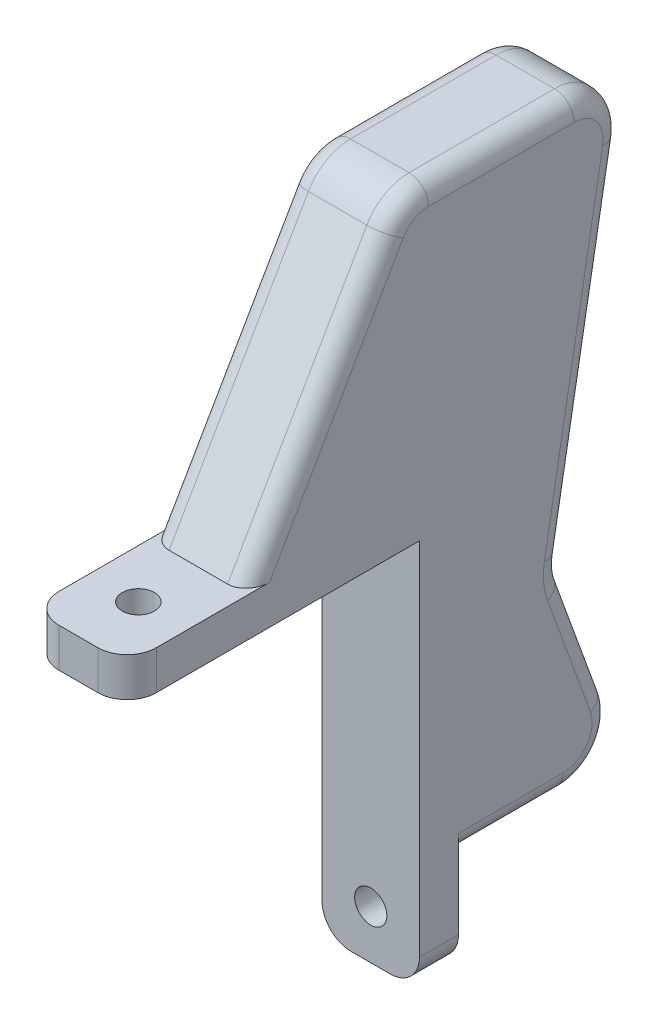
SolidWorks part; units mm, degrees
ref_plane "Front Plane" through (0, 0, 0) normal (0, 0, 1) x (1, 0, 0)
ref_plane "Top Plane" through (0, 0, 0) normal (0, 1, 0) x (1, 0, 0)
ref_plane "Right Plane" through (0, 0, 0) normal (1, 0, 0) x (0, 0, -1)
sketch "Sketch1" plane through (0, 0, 0) normal (1, 0, 0) x (0, 0, -1)
  line L0 (0, 0) -> (20, 0)
  line L1 (0, 0) -> (18.0413, 31.2484)
  line L2 (18.0413, 31.2484) -> (41.8095, 31.2484)
  line L4 (41.8684, -30) -> (20, -30)
  line L6 (20, 0) -> (20, -30)
  line L8 (20, -30) -> (32.0088, -30) construction
  line L9 (41.8095, 31.2484) -> (34.5535, -9.9026)
  line L10 (34.5535, -9.9026) -> (41.8684, -30)
  point P7 (34.5535, -9.9026)
  dimension "D1" = 20
  dimension "D2" = 60
  dimension "D3" = 70
  dimension "D4" = 80
  dimension "D7" = 30
extrude "Boss-Extrude1" add sketch "Sketch1" along normal blind 10
fillet "Fillet1" radius 5 4 edges at (5, -30, -41.8684) (5, -9.9026, -34.5535) (5, 31.2484, -41.8095) (5, 31.2484, -18.0413)
sketch "Sketch2" plane through (0, 0, 0) normal (0, -1, 0) x (1, 0, 0)
  line L0 (0, -20) -> (0, 0)
  line L1 (0, 0) -> (0, 10)
  line L2 (0, 10) -> (10, 10)
  line L3 (10, 10) -> (10, 0)
  line L4 (10, 0) -> (10, -20)
  line L5 (10, -20) -> (0, -20)
  line L6 (10, 0) -> (0, 0) construction
extrude "Boss-Extrude2" add sketch "Sketch2" against normal blind 4
sketch "Sketch3" plane through (0, 4, 0) normal (0, 1, 0) x (1, 0, 0)
  line L0 (5, -10) -> (5, 2.3094) construction
  line L1 (10, -10) -> (0, -10) construction
  line L2 (0, 2.3094) -> (10, 2.3094) construction
  circle A0 centre (5, -3.8453) radius 1.65
  dimension "D1" = 3.3
extrude "Cut-Extrude1" cut sketch "Sketch3" against normal through all
sketch "Sketch4" plane through (0, 0, -20) normal (0, 0, 1) x (1, 0, 0)
  line L0 (0, 0) -> (0, -30)
  line L1 (0, -30) -> (0, -40)
  line L2 (0, -40) -> (10, -40)
  line L3 (10, -40) -> (10, -30)
  line L4 (10, -30) -> (10, 0)
  line L5 (10, 0) -> (0, 0)
  line L6 (10, -30) -> (0, -30) construction
extrude "Boss-Extrude3" add sketch "Sketch4" against normal blind 4
sketch "Sketch5" plane through (0, 0, -24) normal (0, 0, -1) x (-1, 0, 0)
  line L0 (-5, -30) -> (-5, -40) construction
  line L1 (0, -30) -> (-10, -30) construction
  line L2 (0, -40) -> (-10, -40) construction
  circle A0 centre (-5, -35) radius 1.65
  dimension "D1" = 3.3
extrude "Cut-Extrude2" cut sketch "Sketch5" against normal through all
fillet "Fillet2" radius 3 4 edges at (0, -40, -22) (10, -40, -22) (0, 2, 10) (10, 2, 10)
fillet "Fillet3" radius 2 18 edges at (0, -30, -29.3638) (0, -27.8679, -38.8234) (0, -17.2257, -37.2189) (0, -9.8872, -34.7292) (0, 8.3985, -37.7805) (0, 29.4623, -39.681) (0, 31.2484, -28.3894) (0, 30.5785, -18.428) (10, -30, -29.3638) (10, -27.8679, -38.8234) (10, -17.2257, -37.2189) (10, -9.8872, -34.7292) (10, 8.3985, -37.7805) (10, 29.4623, -39.681) (10, 31.2484, -28.3894) (10, 30.5785, -18.428) (0, 16.3742, -9.4537) (10, 16.3742, -9.4537)
